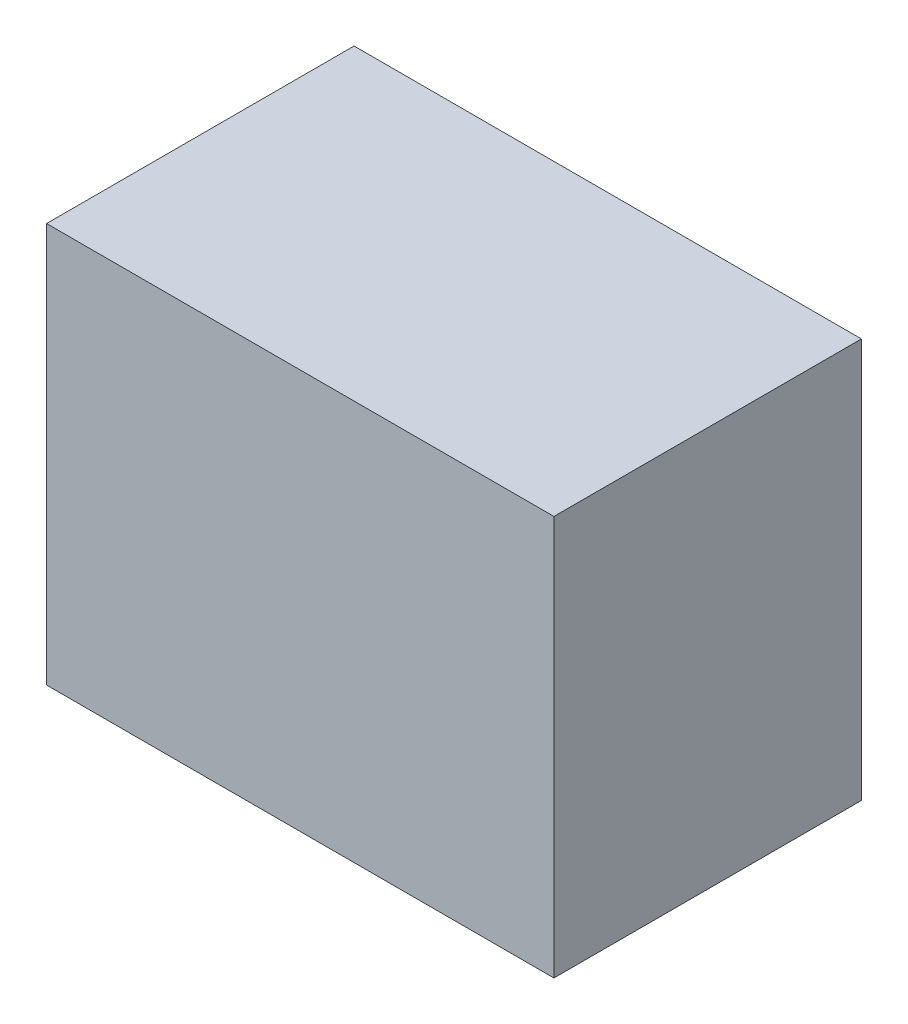
SolidWorks part; units mm, degrees
ref_plane "Спереди" through (0, 0, 0) normal (0, 0, 1) x (1, 0, 0)
ref_plane "Сверху" through (0, 0, 0) normal (0, 1, 0) x (1, 0, 0)
ref_plane "Справа" through (0, 0, 0) normal (1, 0, 0) x (0, 0, -1)
sketch "Эскиз1" plane through (0, 0, 0) normal (0, 0, 1) x (1, 0, 0)
  line L0 (-8.25, 6.5) -> (8.25, 6.5)
  line L1 (-8.25, 6.5) -> (-8.25, -6.5)
  line L2 (-8.25, -6.5) -> (8.25, -6.5)
  line L3 (8.25, 6.5) -> (8.25, -6.5)
extrude "Бобышка-Вытянуть1" add sketch "Эскиз1" along normal blind 10
